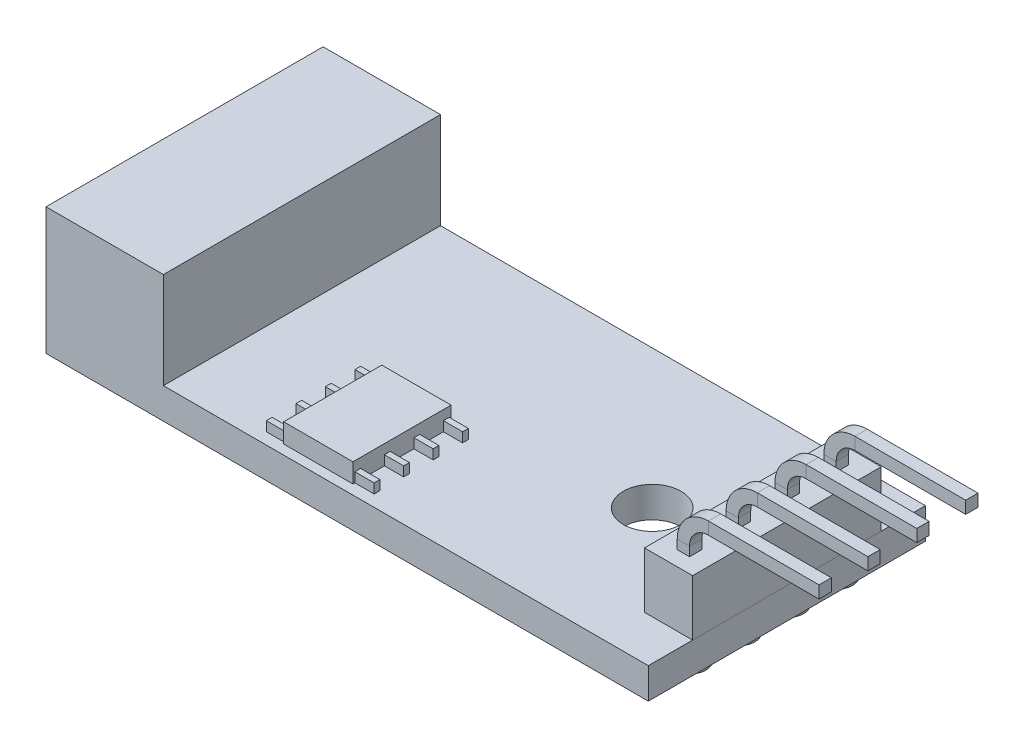
SolidWorks part; units mm, degrees
other "PCB"
other "GND"
other "D0"
other "A0"
other "LM393"
ref_plane "Alzado" through (0, 0, 0) normal (0, 0, 1) x (1, 0, 0)
ref_plane "Planta" through (0, 0, 0) normal (0, 1, 0) x (1, 0, 0)
ref_plane "Vista lateral" through (0, 0, 0) normal (1, 0, 0) x (0, 0, -1)
sketch "Croquis1" plane through (0, 0, 0) normal (0, 1, 0) x (1, 0, 0)
  line L1 (-15.65, -7.2) -> (15.65, -7.2)
  line L2 (-15.65, -7.2) -> (-15.65, 7.2)
  line L3 (-15.65, 7.2) -> (15.65, 7.2)
  line L4 (15.65, -7.2) -> (15.65, 7.2)
  line L5 (-15.65, -7.2) -> (15.65, 7.2) construction
  line L6 (-15.65, 7.2) -> (15.65, -7.2) construction
  circle A0 centre (8.65, 0) radius 1.5
  point P0 (0, 0)
  dimension "D3" = 3
  dimension "D4" = 5.5
  dimension "D1" = 31.3
  dimension "D2" = 14.4
extrude "BASE" add sketch "Croquis1" along normal blind 1.6
sketch "Croquis2" plane through (0, 1.6, 0) normal (0, 1, 0) x (1, 0, 0)
  line L0 (15.65, -7.2) -> (15.65, 7.2) construction
  line L1 (13.15, -4.9) -> (15.65, -4.9)
  line L2 (13.15, -4.9) -> (13.15, 4.9)
  line L3 (13.15, 4.9) -> (15.65, 4.9)
  line L4 (15.65, -4.9) -> (15.65, 4.9)
  line L5 (13.15, -4.9) -> (15.65, 4.9) construction
  line L6 (13.15, 4.9) -> (15.65, -4.9) construction
  line L7 (14.4, 3.81) -> (14.4, 1.27) construction
  line L8 (14.4, 1.27) -> (14.4, -1.27) construction
  line L9 (14.4, -1.27) -> (14.4, -3.81) construction
  point P0 (14.4, 0)
  point P7 (14.4, 3.81)
  point P9 (14.4, 1.27)
  point P10 (14.4, -1.27)
  point P11 (14.4, -3.81)
  point P14 (14.4, 0)
  dimension "D1" = 2.5
  dimension "D2" = 9.8
  dimension "D3" = 2.54
extrude "BASE PINES" add sketch "Croquis2" along normal blind 2.9 separate body
ref_plane "PLANO PIN Vcc" through (0, 0, -3.81) normal (0, 0, 1) x (1, 0, 0)
sketch "DIRECTRIZ" plane through (0, 0, -3.81) normal (0, 0, 1) x (1, 0, 0)
  line L0 (14.4, 4.5) -> (14.4, 4.98)
  line L1 (13.15, 4.5) -> (15.65, 4.5) construction
  line L2 (15.7, 6.28) -> (21.45, 6.28)
  line L3 (13.15, 4.5) -> (13.15, 1.6) construction
  line L4 (21.45, 6.6) -> (21.45, 5.96) construction
  line L5 (-15.65, 0) -> (15.65, 0) construction
  arc A0 (14.4, 4.98) -> (15.7, 6.28) centre (15.7, 4.98) cw
  point P11 (21.45, 6.28)
  dimension "D4" = 1.3
  dimension "D1" = 8.3
  dimension "D2" = 0.64
  dimension "D3" = 6.6
sketch "SECCION" plane through (0, 4.5, 0) normal (0, 1, 0) x (1, 0, 0)
  line L1 (14.08, 4.13) -> (14.72, 4.13)
  line L2 (14.08, 4.13) -> (14.08, 3.49)
  line L3 (14.08, 3.49) -> (14.72, 3.49)
  line L4 (14.72, 4.13) -> (14.72, 3.49)
  line L5 (14.08, 4.13) -> (14.72, 3.49) construction
  line L6 (14.08, 3.49) -> (14.72, 4.13) construction
  point P0 (14.4, 3.81)
  dimension "D1" = 0.64
  dimension "D2" = 0.64
sweep "PIN Vcc" add profiles "SECCION" path "DIRECTRIZ"
pattern_linear "MatrizL1" count 4 spacing 2.54 along (0, 0, 1) of bodies 103
sketch "Croquis5" plane through (0, 1.6, 0) normal (0, 1, 0) x (1, 0, 0)
  line L0 (-15.65, -7.2) -> (15.65, -7.2) construction
  line L1 (-15.65, 7.2) -> (-9.55, 7.2)
  line L2 (-15.65, 7.2) -> (-15.65, -7.2)
  line L3 (-15.65, -7.2) -> (-9.55, -7.2)
  line L4 (-9.55, 7.2) -> (-9.55, -7.2)
  dimension "D1" = 6.1
sketch "Croquis7" plane through (0, 1.6, 0) normal (0, 1, 0) x (1, 0, 0)
  line L0 (-15.65, -7.2) -> (15.65, -7.2) construction
  line L1 (-3.8, -1.6) -> (-0.2, -1.6)
  line L2 (-3.8, -1.6) -> (-3.8, -6.7)
  line L3 (-3.8, -6.7) -> (-0.2, -6.7)
  line L4 (-0.2, -1.6) -> (-0.2, -6.7)
  line L5 (-3.8, -1.6) -> (-0.2, -6.7) construction
  line L6 (-3.8, -6.7) -> (-0.2, -1.6) construction
  point P0 (-2, -4.15)
  dimension "D1" = 2
  dimension "D2" = 0.5
  dimension "D3" = 3.6
  dimension "D4" = 5.1
extrude "Saliente-Extruir4" add sketch "Croquis7" along normal blind 1 separate body
sketch "Croquis8" plane through (0, 1.6, 0) normal (0, 1, 0) x (1, 0, 0)
  line L0 (-3.8, -1.6) -> (-3.8, -6.7) construction
  line L1 (-4.8, -1.7) -> (-3.8, -1.7)
  line L2 (-4.8, -1.7) -> (-4.8, -2)
  line L3 (-4.8, -2) -> (-3.8, -2)
  line L4 (-3.8, -1.7) -> (-3.8, -2)
  line L5 (-0.2, -6.7) -> (-0.2, -1.6) construction
  line L6 (-4.8, -3.2333) -> (-3.8, -3.2333)
  line L7 (-4.8, -3.2333) -> (-4.8, -3.5333)
  line L8 (-4.8, -3.5333) -> (-3.8, -3.5333)
  line L9 (-3.8, -3.2333) -> (-3.8, -3.5333)
  line L10 (-4.8, -4.7667) -> (-3.8, -4.7667)
  line L11 (-4.8, -4.7667) -> (-4.8, -5.0667)
  line L12 (-4.8, -5.0667) -> (-3.8, -5.0667)
  line L13 (-3.8, -4.7667) -> (-3.8, -5.0667)
  line L14 (-4.8, -6.3) -> (-3.8, -6.3)
  line L15 (-4.8, -6.3) -> (-4.8, -6.6)
  line L16 (-4.8, -6.6) -> (-3.8, -6.6)
  line L17 (-3.8, -6.3) -> (-3.8, -6.6)
  line L18 (0.8, -1.7) -> (-0.2, -1.7)
  line L19 (0.8, -1.7) -> (0.8, -2)
  line L20 (0.8, -2) -> (-0.2, -2)
  line L21 (-0.2, -1.7) -> (-0.2, -2)
  line L22 (-0.2, -1.6) -> (-3.8, -1.6) construction
  line L23 (0.8, -3.2333) -> (-0.2, -3.2333)
  line L24 (0.8, -3.2333) -> (0.8, -3.5333)
  line L25 (0.8, -3.5333) -> (-0.2, -3.5333)
  line L26 (-0.2, -3.2333) -> (-0.2, -3.5333)
  line L27 (0.8, -4.7667) -> (-0.2, -4.7667)
  line L28 (0.8, -4.7667) -> (0.8, -5.0667)
  line L29 (0.8, -5.0667) -> (-0.2, -5.0667)
  line L30 (-0.2, -4.7667) -> (-0.2, -5.0667)
  line L31 (0.8, -6.3) -> (-0.2, -6.3)
  line L32 (0.8, -6.3) -> (0.8, -6.6)
  line L33 (0.8, -6.6) -> (-0.2, -6.6)
  line L34 (-0.2, -6.3) -> (-0.2, -6.6)
  line L35 (-4.8, -2) -> (-4.8, -3.2333) construction
  line L36 (-4.8, -3.5333) -> (-4.8, -4.7667) construction
  line L37 (-4.8, -5.0667) -> (-4.8, -6.3) construction
  line L38 (-3.8, -6.7) -> (-0.2, -6.7) construction
  dimension "D1" = 0.1
  dimension "D2" = 0.3
  dimension "D3" = 1
  dimension "D4" = 0.1
extrude "Saliente-Extruir5" add sketch "Croquis8" along normal blind 0.5
sketch "Croquis9" plane through (0, 0, 0) normal (0, -1, 0) x (1, 0, 0)
  line L0 (-10.575, 5.15) -> (-13.15, 5.15) construction
  line L1 (-13.15, 5.15) -> (-13.15, 2.575) construction
  line L2 (-13.15, 2.575) -> (-13.15, 0) construction
  line L3 (-13.15, 0) -> (-13.15, -2.575) construction
  line L4 (-13.15, -2.575) -> (-13.15, -5.15) construction
  line L5 (-13.15, -5.15) -> (-10.575, -5.15) construction
  line L6 (-10.575, -5.15) -> (-10.575, -2.575) construction
  line L7 (-10.575, 5.15) -> (-10.575, 2.575) construction
  line L8 (-15.65, -7.2) -> (-15.65, 7.2) construction
  circle A0 centre (-13.15, 5.15) radius 0.85
  circle A1 centre (-10.575, 5.15) radius 0.85
  circle A2 centre (-10.575, 2.575) radius 0.85
  circle A3 centre (-13.15, 2.575) radius 0.85
  circle A4 centre (-13.15, 0) radius 0.85
  circle A5 centre (-13.15, -2.575) radius 0.85
  circle A6 centre (-13.15, -5.15) radius 0.85
  circle A7 centre (-10.575, -5.15) radius 0.85
  circle A8 centre (-10.575, -2.575) radius 0.85
  circle A9 centre (14.4, 3.81) radius 0.85
  circle A10 centre (14.4, 1.27) radius 0.85
  circle A11 centre (14.4, -1.27) radius 0.85
  circle A12 centre (14.4, -3.81) radius 0.85
  dimension "D1" = 1.7
  dimension "D2" = 12
  dimension "D3" = 2.5
extrude "Saliente-Extruir6" add sketch "Croquis9" along normal blind 0.5
extrude "Boss-Extrude1" add sketch "Croquis5" along normal blind 5
